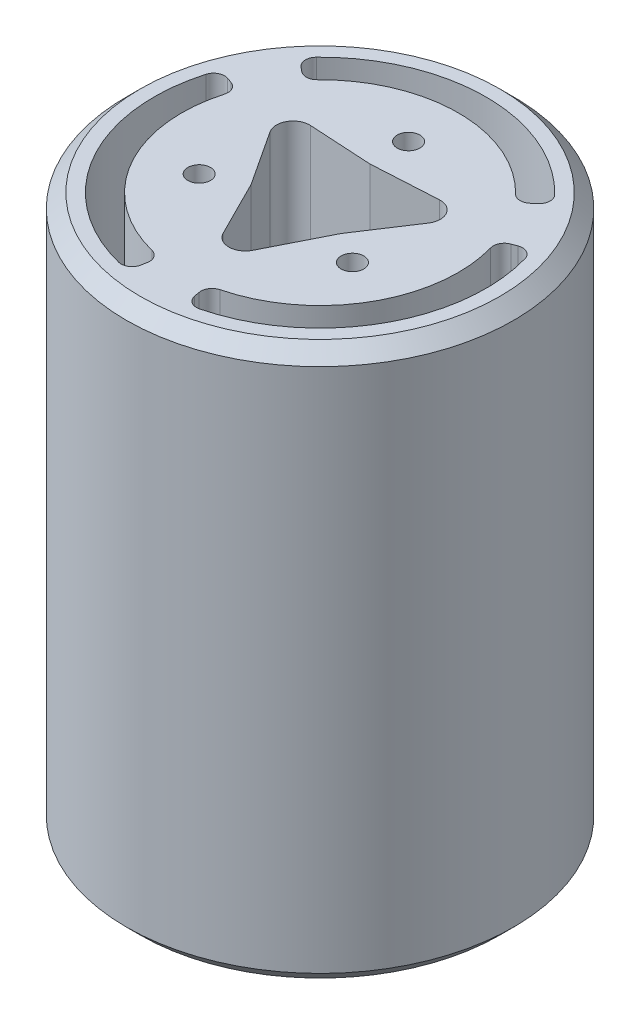
SolidWorks part; units mm, degrees
ref_plane "正面" through (0, 0, 0) normal (0, 0, 1) x (1, 0, 0)
ref_plane "平面" through (0, 0, 0) normal (0, 1, 0) x (1, 0, 0)
ref_plane "右側面" through (0, 0, 0) normal (1, 0, 0) x (0, 0, -1)
sketch "ｽｹｯﾁ1" plane through (0, 0, 0) normal (0, 1, 0) x (1, 0, 0)
  circle A0 centre (0, 0) radius 35
  dimension "D1" = 70
extrude "ﾎﾞｽ - 押し出し1" add sketch "ｽｹｯﾁ1" along normal blind 100
sketch "ｽｹｯﾁ2" plane through (0, 100, 0) normal (0, 1, 0) x (1, 0, 0)
  line L0 (0, 16) -> (0, 0) construction
  line L1 (13.8564, -8) -> (0, 0) construction
  line L2 (-13.8564, -8) -> (0, 0) construction
  circle A0 centre (0, 16) radius 2.05
  circle A1 centre (13.8564, -8) radius 2.05
  circle A2 centre (-13.8564, -8) radius 2.05
  dimension "D1" = 16
  dimension "D2" = 4.1
  dimension "D3" = 3
extrude "ｶｯﾄ - 押し出し1" cut sketch "ｽｹｯﾁ2" against normal blind 5
chamfer "面取り1" distance 2.5 angle 45 2 edges at (0, 0, 35) (0, 100, 35)
sketch "ｽｹｯﾁ3" plane through (0, 0, 0) normal (0, -1, 0) x (1, 0, 0)
  line L0 (0, 0) -> (0, -16) construction
  line L1 (13.8564, 8) -> (0, 0) construction
  line L2 (0, 0) -> (-13.8564, 8) construction
  circle A0 centre (0, -16) radius 2.05
  circle A1 centre (-13.8564, 8) radius 2.05
  circle A2 centre (13.8564, 8) radius 2.05
  dimension "D1" = 16
  dimension "D2" = 4.1
  dimension "D3" = 3
extrude "ｶｯﾄ - 押し出し2" cut sketch "ｽｹｯﾁ3" against normal blind 5
sketch "ｽｹｯﾁ4" plane through (0, 100, 0) normal (0, 1, 0) x (1, 0, 0)
  line L0 (-22.9813, 19.2836) -> (0, 0) construction
  line L1 (0, 0) -> (0, 30) construction
  line L2 (22.9813, 19.2836) -> (0, 0) construction
  line L3 (-21.3945, 17.9521) -> (-20.6264, 17.3076)
  line L4 (21.3945, 17.9521) -> (20.6264, 17.3076)
  line L5 (4.8497, -27.5042) -> (4.6756, -26.5168)
  line L6 (26.2442, 9.5521) -> (25.302, 9.2092)
  line L7 (-26.2442, 9.5521) -> (-25.302, 9.2092)
  line L8 (-4.8497, -27.5042) -> (-4.6756, -26.5168)
  line L9 (0, 0) -> (-28.1458, 16.25) construction
  line L10 (-7.526, -4.9355) -> (-14.0523, 5.0163)
  line L11 (-11.3707, 9.6565) -> (0, 9)
  line L12 (0, 9) -> (11.8816, 9.676)
  line L13 (14.5593, 5.0336) -> (8.3055, -4.4855)
  line L14 (8.3055, -4.4855) -> (2.9501, -15.1133)
  line L15 (-2.4092, -15.111) -> (-7.526, -4.9355)
  arc A0 (21.5452, 20.8759) -> (-21.5452, 20.8759) centre (0, 0) ccw
  arc A1 (17.9082, 17.4441) -> (-17.9082, 17.4441) centre (0, 0) ccw
  arc A2 (21.5452, 20.8759) -> (21.3945, 17.9521) centre (20.1089, 19.4842) cw
  arc A3 (17.9082, 17.4441) -> (20.6264, 17.3076) centre (19.3408, 18.8397) ccw
  arc A4 (-17.9082, 17.4441) -> (-20.6264, 17.3076) centre (-19.3408, 18.8397) cw
  arc A5 (-21.5452, 20.8759) -> (-21.3945, 17.9521) centre (-20.1089, 19.4842) ccw
  arc A6 (6.153, -24.231) -> (4.6756, -26.5168) centre (6.6452, -26.1695) ccw
  arc A7 (7.3064, -29.0967) -> (4.8497, -27.5042) centre (6.8193, -27.1569) cw
  arc A8 (6.153, -24.231) -> (24.0611, 6.7868) centre (0, 0) ccw
  arc A9 (24.0611, 6.7868) -> (25.302, 9.2092) centre (25.986, 7.3298) cw
  arc A10 (28.8517, 8.2208) -> (26.2442, 9.5521) centre (26.9282, 7.6727) ccw
  arc A11 (7.3064, -29.0967) -> (28.8517, 8.2208) centre (0, 0) ccw
  arc A12 (-24.0611, 6.7868) -> (-25.302, 9.2092) centre (-25.986, 7.3298) ccw
  arc A13 (-28.8517, 8.2208) -> (-26.2442, 9.5521) centre (-26.9282, 7.6727) cw
  arc A14 (-24.0611, 6.7868) -> (-6.153, -24.231) centre (0, 0) ccw
  arc A15 (-6.153, -24.231) -> (-4.6756, -26.5168) centre (-6.6452, -26.1695) cw
  arc A16 (-7.3064, -29.0967) -> (-4.8497, -27.5042) centre (-6.8193, -27.1569) ccw
  arc A17 (-28.8517, 8.2208) -> (-7.3064, -29.0967) centre (0, 0) ccw
  circle A18 centre (0, 0) radius 9 construction
  circle A19 centre (0, 0) radius 32.5 construction
  arc A20 (-14.0523, 5.0163) -> (-11.3707, 9.6565) centre (-11.5436, 6.6615) cw
  arc A21 (11.8816, 9.676) -> (14.5593, 5.0336) centre (12.052, 6.6808) cw
  arc A22 (2.9501, -15.1133) -> (-2.4092, -15.111) centre (0.271, -13.7633) cw
  point P12 (19.1511, 16.0697)
  point P15 (-19.1511, 16.0697)
  point P52 (-17.3205, 10)
  point P53 (-7.3746, -5.159)
  dimension "D1" = 100
  dimension "D2" = 50
  dimension "D3" = 60
  dimension "D4" = 2
  dimension "D6" = 18
  dimension "D9" = 3
  dimension "D7" = 60
  dimension "D8" = 20
  dimension "D5" = 3
  dimension "D10" = 3
extrude "ｶｯﾄ - 押し出し3" cut sketch "ｽｹｯﾁ4" against normal through all
